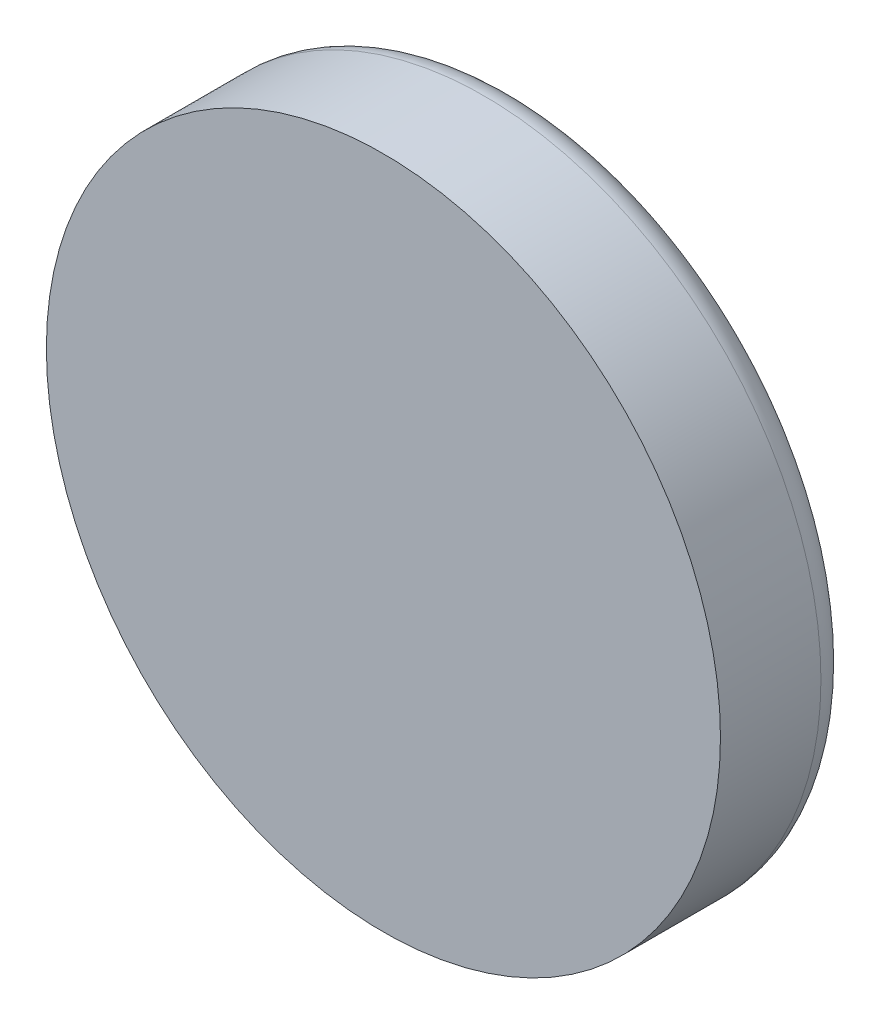
SolidWorks part; units mm, degrees
ref_plane "Front Plane" through (0, 0, 0) normal (0, 0, 1) x (1, 0, 0)
ref_plane "Top Plane" through (0, 0, 0) normal (0, 1, 0) x (1, 0, 0)
ref_plane "Right Plane" through (0, 0, 0) normal (1, 0, 0) x (0, 0, -1)
sketch "Sketch1" plane through (0, 0, 0) normal (0, 0, 1) x (1, 0, 0)
  circle A0 centre (98.5561, 33.3375) radius 17.4625
  circle A1 centre (98.5561, 33.3375) radius 19.05 construction
  dimension "D1" = 1.5875
ref_plane "Plane1" through (0, 33.3375, 0) normal (0, 1, 0) x (1, 0, 0)
sketch "Sketch2" plane through (0, 33.3375, 0) normal (0, 1, 0) x (1, 0, 0)
  line L0 (98.5561, 25.4) -> (98.5561, 34.925)
  line L1 (117.6061, 25.4) -> (79.5061, 25.4) construction
  line L2 (98.5561, 25.4) -> (81.0936, 25.4)
  line L3 (81.0936, 25.4) -> (81.0936, 30.6057)
  line L4 (117.6061, 31.75) -> (79.5061, 31.75) construction
  arc A0 (98.5561, 34.925) -> (82.1942, 32.1167) centre (100.2152, -23.8093) ccw
  arc A1 (81.0936, 30.6057) -> (82.1942, 32.1167) centre (82.6811, 30.6057) cw
  point P11 (81.0936, 31.75)
  dimension "D2" = 1.5875
  dimension "D1" = 17.4625
  dimension "D3" = 9.525
revolve "Revolve1" add sketch "Sketch2" angle 360 about L0
